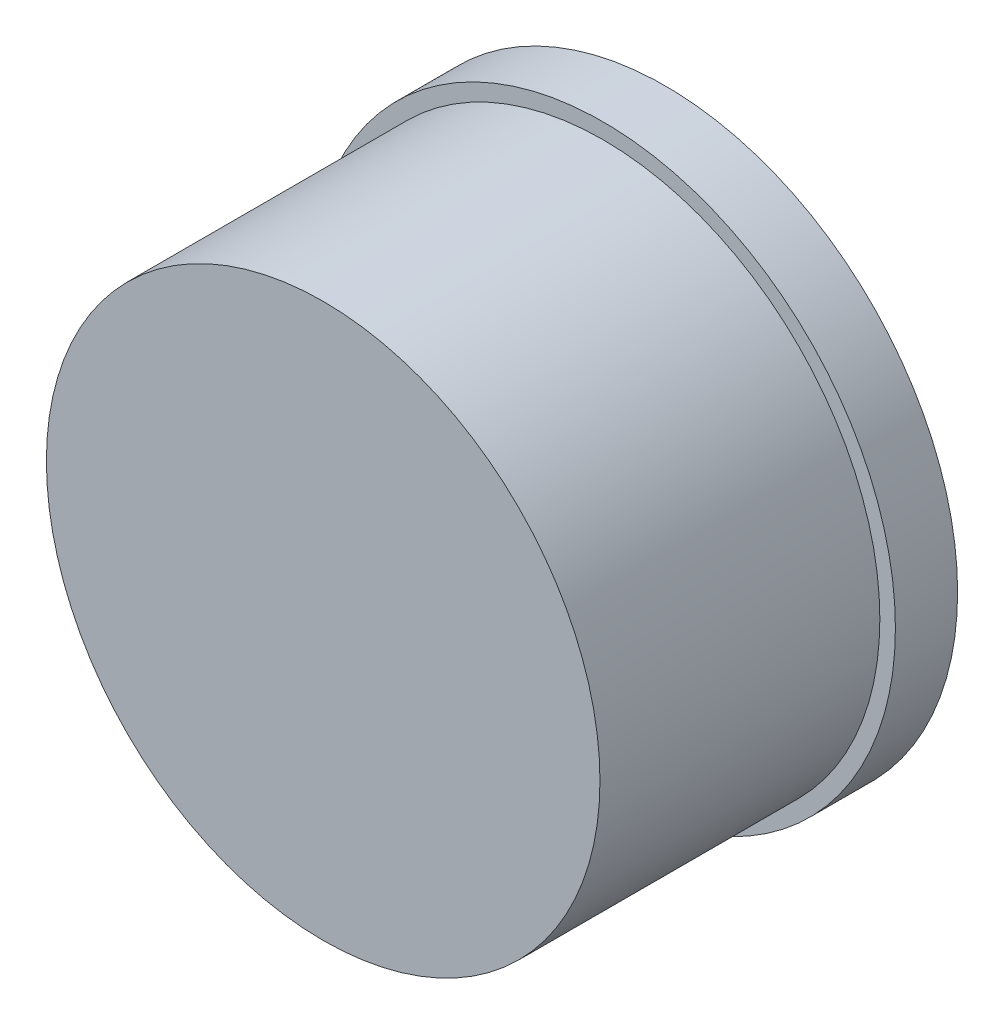
SolidWorks part; units mm, degrees
ref_plane "Front Plane" through (0, 0, 0) normal (0, 0, 1) x (1, 0, 0)
ref_plane "Top Plane" through (0, 0, 0) normal (0, 1, 0) x (1, 0, 0)
ref_plane "Right Plane" through (0, 0, 0) normal (1, 0, 0) x (0, 0, -1)
sketch "Sketch1" plane through (0, 0, 0) normal (0, 0, 1) x (1, 0, 0)
  circle A0 centre (-36.0769, 25.7883) radius 4.7
extrude "Boss-Extrude1" add sketch "Sketch1" along normal blind 1 contours A0
sketch "Sketch2" plane through (0, 0, 1) normal (0, 0, 1) x (1, 0, 0)
  circle A0 centre (-36.0769, 25.7883) radius 4.45
  circle A1 centre (-36.0769, 25.7883) radius 4.7 construction
  dimension "D1" = 0
  dimension "D2" = 0
extrude "Boss-Extrude2" add sketch "Sketch2" along normal blind 4.5 contours A0
